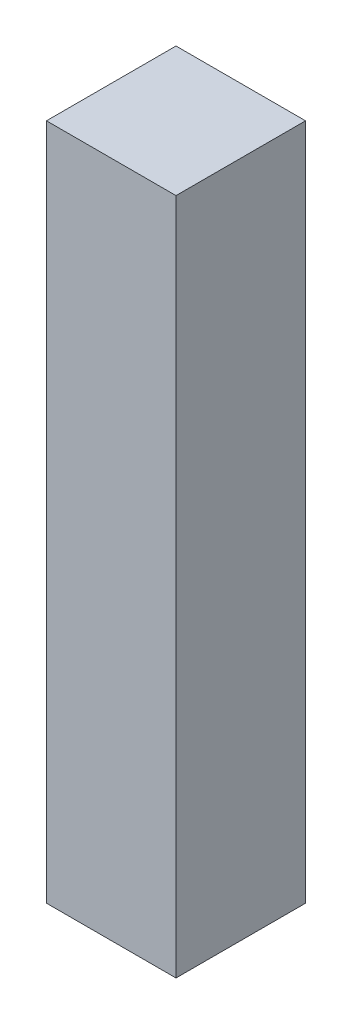
SolidWorks part; units mm, degrees
ref_plane "Front Plane" through (0, 0, 0) normal (0, 0, 1) x (1, 0, 0)
ref_plane "Top Plane" through (0, 0, 0) normal (0, 1, 0) x (1, 0, 0)
ref_plane "Right Plane" through (0, 0, 0) normal (1, 0, 0) x (0, 0, -1)
sketch "Sketch1" plane through (0, 0, 0) normal (0, 1, 0) x (1, 0, 0)
  line L1 (-41.275, 41.275) -> (41.275, 41.275)
  line L2 (-41.275, 41.275) -> (-41.275, -41.275)
  line L3 (-41.275, -41.275) -> (41.275, -41.275)
  line L4 (41.275, 41.275) -> (41.275, -41.275)
  line L5 (-41.275, 41.275) -> (41.275, -41.275) construction
  line L6 (-41.275, -41.275) -> (41.275, 41.275) construction
  point P0 (0, 0)
  dimension "D1" = 82.55
extrude "Boss-Extrude1" add sketch "Sketch1" along normal blind 431.8
